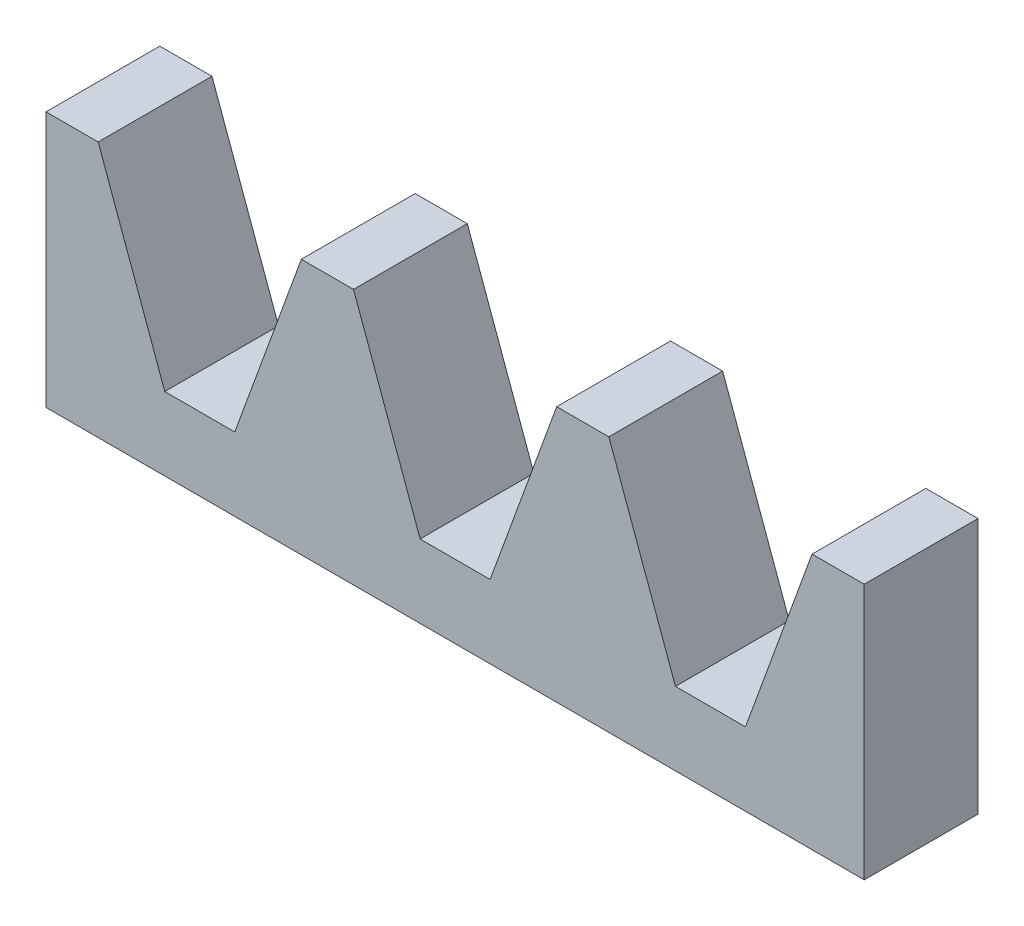
SolidWorks part; units mm, degrees
extrude "Blank" add sketch "BlankSke" against normal blind 2.8
sketch "BlankSke" plane through (0, 0, 0) normal (0, 0, 1) x (1, 0, 0)
  line L1 (0, 0) -> (24, 0)
  line L2 (0, 0) -> (0, 6.3)
  line L3 (0, 6.3) -> (24, 6.3)
  line L4 (24, 0) -> (24, 6.3)
  dimension "Length" = 24
  dimension "Blank_height" = 6.3
ref_plane "Plane1" through (0, 0, 0) normal (0, 0, 1) x (1, 0, 0)
ref_plane "Plane2" through (0, 0, 0) normal (0, 1, 0) x (1, 0, 0)
ref_plane "Plane3" through (0, 0, 0) normal (1, 0, 0) x (0, 0, -1)
sketch "HoldingSke" plane through (0, 0, 0) normal (0, 1, 0) x (1, 0, 0)
  line L0 (0, 0) -> (0.0696, 0.4951)
  line L1 (-15, 0) -> (100, 0) construction
  line L2 (0, 0) -> (-2.1039, 2.3779)
  line L3 (0, 0) -> (-11.863, 4.5341)
  line L4 (0, 0) -> (8.6031, 0.7527)
  line L5 (0, 0) -> (-23.7986, -8.8762)
  line L6 (0, 0) -> (-10.5278, -7.1032)
  line L9 (-71.009, 38.7566) -> (-48.4563, 46.9651)
  line L10 (-76.2, 4.3779) -> (-71.9, 4.3779)
  line L11 (0, 0) -> (-2.8, 0)
  line L12 (-76.2, 101.6) -> (-76.133, 101.6)
  line L13 (24.9733, 27.94) -> (52.9518, 28.4284)
  line L14 (24.9733, 27.94) -> (24.9743, 27.94)
  line L15 (24.9733, 27.94) -> (100.4006, 29.5858)
  circle A0 centre (0, 0) radius 19.05
  circle A1 centre (0, 0) radius 2.15
  circle A2 centre (0, 0) radius 12.7
  dimension "MPH" = 4.3
  dimension "Diameter" = 38.1
  dimension "Num_teeth" = 5
  dimension "Pitch" = 0.5
  dimension "Show_teeth" = 998
  dimension "Thickness" = 12.7
  dimension "Ap" = 20
  dimension "Pitch_height" = 4.3
  dimension "Width" = 2.8
  dimension "Backlash" = 0.067
  dimension "Addendum_fac" = 1
  dimension "Dedendum_fac" = 1.25
  dimension "Clearance_fac" = 0.25
  dimension "Dedendum_add" = 0.001
  dimension "Length" = 24
  dimension "Module" = 2
sketch "TooCutSkeIll" plane through (0, 0, 0) normal (0, 0, 1) x (1, 0, 0)
  line L0 (-2.4806, 6.2474) -> (-0.9819, 2.1296)
  line L1 (-0.5111, 1.8) -> (0.5111, 1.8)
  line L2 (0.9819, 2.1296) -> (2.4806, 6.2474)
  line L3 (24, 6.3) -> (0, 6.3) construction
  line L4 (0, 0) -> (0, 64.897) construction
  line L5 (-13.208, 4.3) -> (12.954, 4.3) construction
  line L6 (0, 0) -> (24, 0) construction
  line L7 (1.7718, 4.3) -> (1.7718, 48.7463) construction
  line L8 (-1.7718, 4.3) -> (-1.7718, 48.7463) construction
  line L9 (2.5558, 6.3) -> (2.5558, 6.3254)
  line L10 (-2.5558, 6.3) -> (-2.5558, 6.3254)
  line L11 (-2.5558, 6.3254) -> (2.5558, 6.3254)
  arc A0 (0.5111, 1.8) -> (0.9819, 2.1296) centre (0.5111, 2.301) ccw
  arc A1 (-0.9819, 2.1296) -> (-0.5111, 1.8) centre (-0.5111, 2.301) ccw
  arc A2 (2.5558, 6.3) -> (2.4806, 6.2474) centre (2.5558, 6.22) ccw
  arc A3 (-2.4806, 6.2474) -> (-2.5558, 6.3) centre (-2.5558, 6.22) ccw
  dimension "Pitch_height" = 4.3
  dimension "Addendum_plus" = 2.0254
  dimension "Pressure_angle" = 20
  dimension "Gap_width" = 3.5436
  dimension "Dedendum" = 2.5
extrude "ToothCutIll" [suppressed] cut sketch "TooCutSkeIll" against normal through all
sketch "TooCutSkeSim" plane through (0, 0, 0) normal (0, 0, 1) x (1, 0, 0)
  line L0 (0.8619, 1.8) -> (-0.8619, 1.8)
  line L1 (2.509, 6.3254) -> (0.8619, 1.8)
  line L2 (0, 17.4625) -> (0, 53.467) construction
  line L3 (2.509, 6.3254) -> (-2.509, 6.3254)
  line L6 (-2.509, 6.3254) -> (-0.8619, 1.8)
  line L9 (-1.7718, 4.3) -> (1.7718, 4.3) construction
  line L10 (0, 0) -> (24, 0) construction
  line L11 (1.7718, 4.3) -> (1.7718, 53.467) construction
  line L12 (-1.7718, 4.3) -> (-1.7718, 53.467) construction
  dimension "Pitch_height" = 4.3
  dimension "Addendum_plus" = 2.0254
  dimension "Pressure_angle" = 20
  dimension "Gap_width" = 3.5436
  dimension "Dedendum" = 2.5
extrude "ToothCutSim" cut sketch "TooCutSkeSim" against normal through all
pattern_linear "TeethCuts" count 4 spacing 6.2832 along (1, 0, 0) of "ToothCutIll", "ToothCutSim"
sketch "ｽｹｯﾁ1" plane through (0, 0, 0) normal (0, 0, 1) x (1, 0, 0)
  line L1 (22.633, 6.3) -> (24, 6.3)
  line L2 (22.633, 6.3) -> (22.633, 0)
  line L3 (22.633, 0) -> (24, 0)
  line L4 (24, 6.3) -> (24, 0)
  line L5 (0, 0) -> (2.4997, 0)
  line L6 (0, 0) -> (0, 6.3)
  line L7 (0, 6.3) -> (2.4997, 6.3)
  line L8 (2.4997, 0) -> (2.4997, 6.3)
extrude "ｶｯﾄ - 押し出し1" cut sketch "ｽｹｯﾁ1" against normal through all
sketch "ｽｹｯﾁ2" plane through (0, 0, 0) normal (0, 0, 1) x (1, 0, 0)
  line L0 (2.4997, 4.3) -> (22.633, 4.3) construction
  line L1 (2.4997, 0) -> (2.4997, 6.3) construction
  line L2 (22.633, 6.3) -> (22.633, 0) construction
  line L3 (2.4997, 0) -> (22.633, 0) construction
  dimension "D1" = 4.3
equation "' \"Module@HoldingSke\" = 6.35"
equation "' \"Num_teeth@HoldingSke\" = 12"
equation "' \"Ap@HoldingSke\" =  20"
equation "' \"Ap@HoldingSke\" = 20"
equation "' \"Width@HoldingSke\" = 0.25 * 25.4"
equation "' \"Show_teeth@HoldingSke\" = 500"
equation "' \"Backlash@HoldingSke\" = 0.009 * 25.4"
equation "' \"Addendum_fac@HoldingSke\" = 1.0"
equation "' \"Dedendum_fac@HoldingSke\" = 1.25"
equation "' \"Dedendum_add@HoldingSke\" = 0.00005 * 25.4"
equation "' \"Clearance_fac@HoldingSke\" = 0.25"
equation "' \"Pitch_height@HoldingSke\" = 1 * 25.4"
equation "' \"Length@HoldingSke\" = 4.71 * 25.4"
equation "\"Pitch@HoldingSke\" = 1 / \"Module@HoldingSke\""
equation "\"MPH@HoldingSke\" = \"Dedendum_fac@HoldingSke\" / \"Pitch@HoldingSke\" + 2 * \"Dedendum_add@HoldingSke\" + 0.002 * 25.4"
equation "\"MPH@HoldingSke\" = ((sgn( \"MPH@HoldingSke\" - \"Pitch_height@HoldingSke\")+1)*( \"MPH@HoldingSke\" - \"Pitch_height@HoldingSke\"))/2 + \"Pitch_height@HoldingSke\""
equation "\"Blank_height@BlankSke\" = \"Pitch_height@HoldingSke\" + \"Addendum_fac@HoldingSke\"  / \"Pitch@HoldingSke\" "
equation "\"Length@BlankSke\" =  \"Length@HoldingSke\""
equation "\"Face_width@Blank\" = \"Width@HoldingSke\""
equation "\"Pressure_angle@TooCutSkeIll\" = \"Ap@HoldingSke\""
equation "\"Addendum_plus@TooCutSkeIll\" =  \"Addendum_fac@HoldingSke\"  / \"Pitch@HoldingSke\" + 0.001 *25.4"
equation "\"Dedendum@TooCutSkeIll\" = \"Dedendum_fac@HoldingSke\"  / \"Pitch@HoldingSke\""
equation "\"Pitch_height@TooCutSkeIll\" =  \"MPH@HoldingSke\""
equation "\"Gap_width@TooCutSkeIll\" = 3.14159265 / 2 / \"Pitch@HoldingSke\" + 6 * \"Backlash@HoldingSke\""
equation "\"Pressure_angle@TooCutSkeSim\" = \"Ap@HoldingSke\""
equation "\"Addendum_plus@TooCutSkeSim\" =  \"Addendum_fac@HoldingSke\"  / \"Pitch@HoldingSke\" + 0.001 * 25.4"
equation "\"Dedendum@TooCutSkeSim\" = \"Dedendum_fac@HoldingSke\"  / \"Pitch@HoldingSke\""
equation "\"Pitch_height@TooCutSkeSim\" =  \"MPH@HoldingSke\""
equation "\"Gap_width@TooCutSkeSim\" = 3.14159265 / 2 / \"Pitch@HoldingSke\" + 6 * \"Backlash@HoldingSke\""
equation "\"Root_fillet@TooCutSkeIll\" = \"Clearance_fac@HoldingSke\" / \"Pitch@HoldingSke\" + \"Dedendum_add@HoldingSke\""
equation "\"Break_rad@TooCutSkeIll\" = 0.02 / \"Pitch@HoldingSke\" * 2"
equation "\"Linear_pitch@TeethCuts\" = 3.14159265 / \"Pitch@HoldingSke\""
equation "\"Num_teeth@HoldingSke\" = int( ( \"Length@HoldingSke\" + 0 ) / (3.14159265 / \"Pitch@HoldingSke\")) + 0.9999  + 1"
equation " \"Num_teeth@TeethCuts\" = int( \"Show_teeth@HoldingSke\" ) + 1"
equation " \"Num_teeth@TeethCuts\" = ((sgn( \"Num_teeth@TeethCuts\" - \"Num_teeth@HoldingSke\" )-1)*( \"Num_teeth@TeethCuts\" - \"Num_teeth@HoldingSke\" ))/-2+ \"Num_teeth@HoldingSke\""
equation " \"Num_teeth@TeethCuts\" = ((sgn( \"Num_teeth@TeethCuts\" - 2.0)+1)*( \"Num_teeth@TeethCuts\" - 2.0))/2 +2.0"
